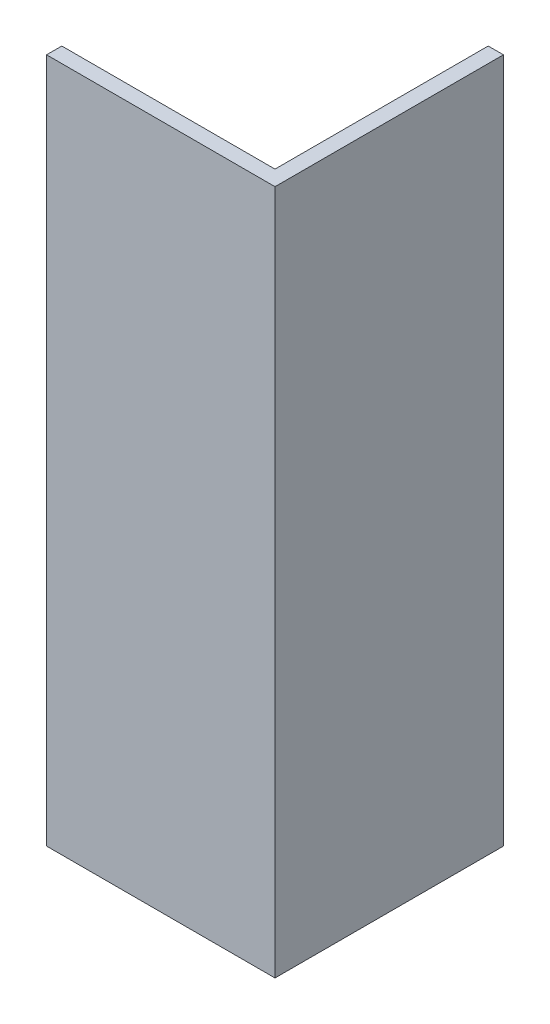
SolidWorks part; units mm, degrees
ref_plane "Front Plane" through (0, 0, 0) normal (0, 0, 1) x (1, 0, 0)
ref_plane "Top Plane" through (0, 0, 0) normal (0, 1, 0) x (1, 0, 0)
ref_plane "Right Plane" through (0, 0, 0) normal (1, 0, 0) x (0, 0, -1)
sketch "Sketch1" plane through (0, 0, 0) normal (0, 1, 0) x (1, 0, 0)
  line L0 (0, 0) -> (0, 0.2)
  line L1 (0, 0.2) -> (2.8, 0.2)
  line L2 (2.8, 0.2) -> (2.8, 3)
  line L3 (2.8, 3) -> (3, 3)
  line L4 (3, 3) -> (3, 0)
  line L5 (3, 0) -> (0, 0)
  dimension "D1" = 0.2
  dimension "D2" = 3
  dimension "D3" = 3
  dimension "D4" = 0.2
extrude "Boss-Extrude1" add sketch "Sketch1" along normal blind 9
